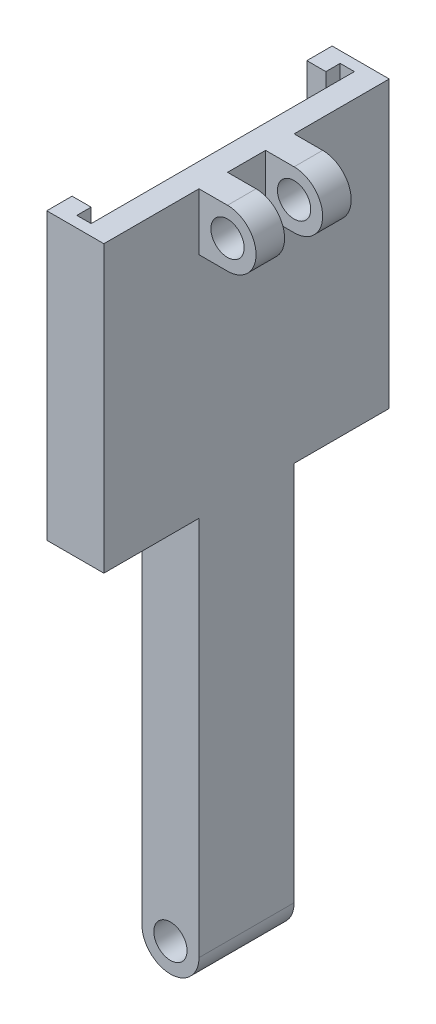
SolidWorks part; units mm, degrees
ref_plane "Front Plane" through (0, 0, 0) normal (0, 0, 1) x (1, 0, 0)
ref_plane "Top Plane" through (0, 0, 0) normal (0, 1, 0) x (1, 0, 0)
ref_plane "Right Plane" through (0, 0, 0) normal (1, 0, 0) x (0, 0, -1)
sketch "Sketch1" plane through (0, 0, 0) normal (0, 0, 1) x (1, 0, 0)
  line L1 (-3, 0) -> (3, 0)
  line L2 (-3, 0) -> (-3, 70)
  line L3 (-3, 70) -> (3, 70)
  line L4 (3, 0) -> (3, 70)
  circle A0 centre (0, 0) radius 1.75
  circle A1 centre (0, 0) radius 3
  dimension "D1" = 3.5
  dimension "D2" = 6
  dimension "D3" = 70
extrude "Boss-Extrude1" add sketch "Sketch1" along normal blind 10 contours A1 L4 L3 L2 | L1 A0 | L1 A0 | L1 A1 A0 | L1 A1 A0
sketch "Sketch2" plane through (-3, 0, 0) normal (-1, 0, 0) x (0, 0, 1)
  line L0 (0, 0) -> (0, 70) construction
  line L1 (-10, 70) -> (20, 70)
  line L2 (-10, 70) -> (-10, 40)
  line L3 (-10, 40) -> (20, 40)
  line L4 (20, 70) -> (20, 40)
  line L5 (10, 70) -> (0, 70) construction
  dimension "D1" = 30
  dimension "D2" = 10
  dimension "D3" = 30
  dimension "D4" = 0
extrude "Boss-Extrude2" add sketch "Sketch2" against normal blind 6
sketch "Sketch3" plane through (0, 70, 0) normal (0, 1, 0) x (1, 0, 0)
  line L0 (-3, -20) -> (-3, 10) construction
  line L1 (-3, 7.3394) -> (-1, 7.3394)
  line L2 (-3, 7.3394) -> (-3, -17.3394)
  line L3 (-3, -17.3394) -> (-1, -17.3394)
  line L4 (-1, 7.3394) -> (-1, -17.3394)
  line L5 (3, -20) -> (3, 10) construction
  line L6 (-1, 8.8394) -> (0.5, 8.8394)
  line L7 (-1, 8.8394) -> (-1, -18.8394)
  line L8 (-1, -18.8394) -> (0.5, -18.8394)
  line L9 (0.5, 8.8394) -> (0.5, -18.8394)
  point P10 (0.5, -5)
  point P13 (3, -5)
  line M11 (-3, 10) -> (-3, -20)
  dimension "D1" = 1.5
  dimension "D2" = 1.5
  dimension "D3" = 27.6789
  dimension "D4" = 0
  dimension "D5" = 1.5
  dimension "D6" = 0
  dimension "D7" = 2
extrude "Cut-Extrude1" cut sketch "Sketch3" against normal blind 28 contours L4 L1 L3 M11 | L9 L6 L7 L4 L8
sketch "Sketch4" plane through (0, 0, 10) normal (0, 0, 1) x (1, 0, 0)
  line L0 (3, 40) -> (3, 70) construction
  line L2 (3, 70) -> (-3, 70) construction
  line L4 (6, 70) -> (3, 70)
  line L5 (6, 70) -> (6, 64)
  line L6 (6, 64) -> (3, 64)
  line L7 (3, 70) -> (3, 64)
  circle A0 centre (6, 67) radius 3
  circle A1 centre (6, 67) radius 1.75
  dimension "D1" = 6
  dimension "D2" = 3.5
  dimension "D3" = 3
  dimension "D4" = 3
extrude "Boss-Extrude3" add sketch "Sketch4" against normal up to surface (10 mm away) contours A1 L5 A0 | A1 L5 A0 | A0 L4 L7 | A0 L7 L6 up to face at (0, 19.25, 0)
sketch "Sketch5" plane through (0, 70, 0) normal (0, 1, 0) x (1, 0, 0)
  line L0 (9, -10) -> (9, 0) construction
  line L1 (9, -3) -> (3, -3)
  line L2 (9, -3) -> (9, -7)
  line L3 (9, -7) -> (3, -7)
  line L4 (3, -3) -> (3, -7)
  line L5 (3, 0) -> (6, 0) construction
  line L6 (6, -10) -> (3, -10) construction
  dimension "D1" = 3
  dimension "D2" = 3
extrude "Cut-Extrude2" cut sketch "Sketch5" against normal up to surface (6 mm away) up to face at (4.5, 64, 5)
